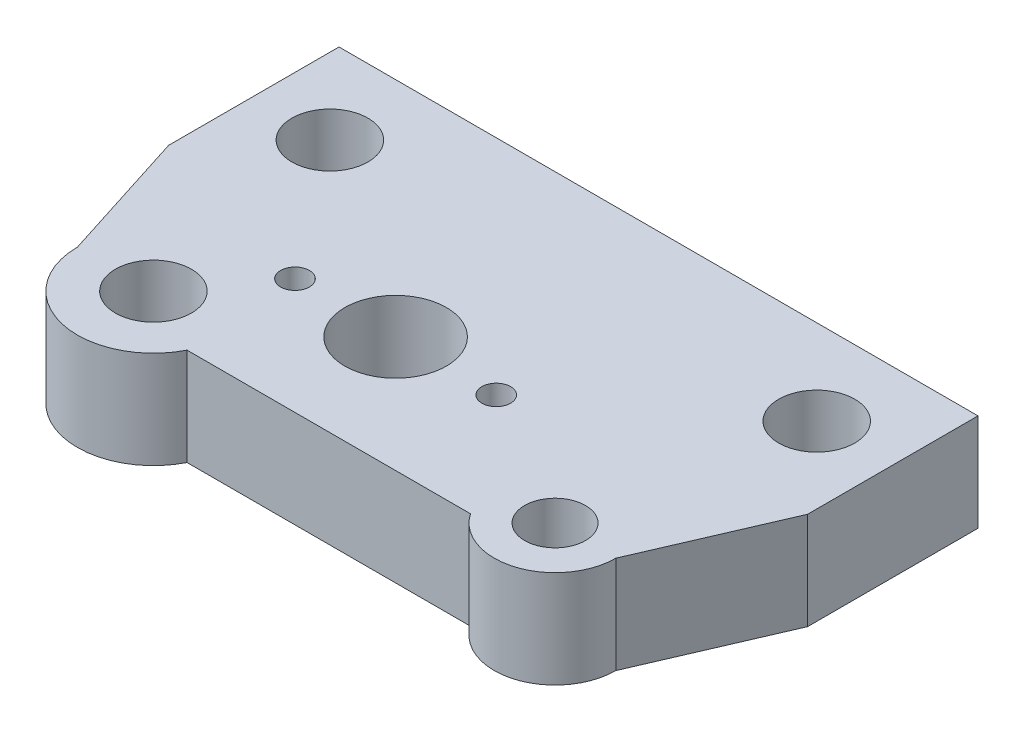
SolidWorks part; units mm, degrees
material "6061-T6 (SS)"
ref_plane "X-Y Datum" through (0, 0, 0) normal (0, 0, 1) x (1, 0, 0)
ref_plane "X-Z Datum" through (0, 0, 0) normal (0, 1, 0) x (1, 0, 0)
ref_plane "Y-Z Datum" through (0, 0, 0) normal (1, 0, 0) x (0, 0, -1)
sketch "Sketch1" plane through (0, 0, 0) normal (0, 1, 0) x (1, 0, 0)
  line L1 (54.2925, 13.97) -> (-12.3825, 13.97) construction
  line L4 (54.2925, 31.75) -> (-12.3825, 31.75)
  line L6 (46.355, 22.86) -> (-4.445, 22.86) construction
  line L7 (54.2925, 31.75) -> (54.2925, 13.97)
  line L8 (-12.3825, 31.75) -> (-12.3825, 13.97)
  line L21 (-7.9375, 0) -> (-12.3825, 13.97)
  line L22 (6.264, 8.509) -> (16.764, 8.509) construction
  line L24 (16.764, 8.509) -> (27.264, 8.509) construction
  line L25 (7.0861, -3.5764) -> (36.6629, -3.5764)
  line L27 (48.26, 0) -> (54.2925, 13.97)
  circle A0 centre (0, 0) radius 3.9688
  circle A1 centre (41.91, 0) radius 3.175
  circle A2 centre (46.355, 22.86) radius 3.9688
  circle A3 centre (-4.445, 22.86) radius 3.9687
  arc A5 (7.0861, -3.5764) -> (-7.9375, 0) centre (0, 0) cw
  circle A7 centre (16.764, 8.509) radius 5.3
  circle A8 centre (6.264, 8.509) radius 1.5
  circle A9 centre (27.264, 8.509) radius 1.5
  arc A10 (36.6629, -3.5764) -> (48.26, 0) centre (41.91, 0) ccw
  dimension "D2" = 6.35
  dimension "D7" = 7.9375
  dimension "D8" = 6.35
  dimension "D12" = 10.6
  dimension "D10" = 7.9375
  dimension "D17" = 3
  dimension "D19" = 7.9375
  dimension "D18" = 7.9375
  dimension "D3" = 50.8
  dimension "D4" = 17.78
  dimension "D5" = 8.89
  dimension "D6" = 31.75
  dimension "D9" = 4.445
  dimension "D11" = 7.9375
  dimension "D13" = 16.764
  dimension "D14" = 5.461
  dimension "D16" = 10.5
  dimension "D20" = 41.91
extrude "Boss-Extrude1" add sketch "Sketch1" against normal blind 10.16
sketch "Sketch3" plane through (0, 0, 0) normal (0, 1, 0) x (1, 0, 0)
  line L0 (0, 0) -> (0, -44.5462) construction
  line L1 (0, 0) -> (26.3151, -45.579) construction
  dimension "D1" = 30
